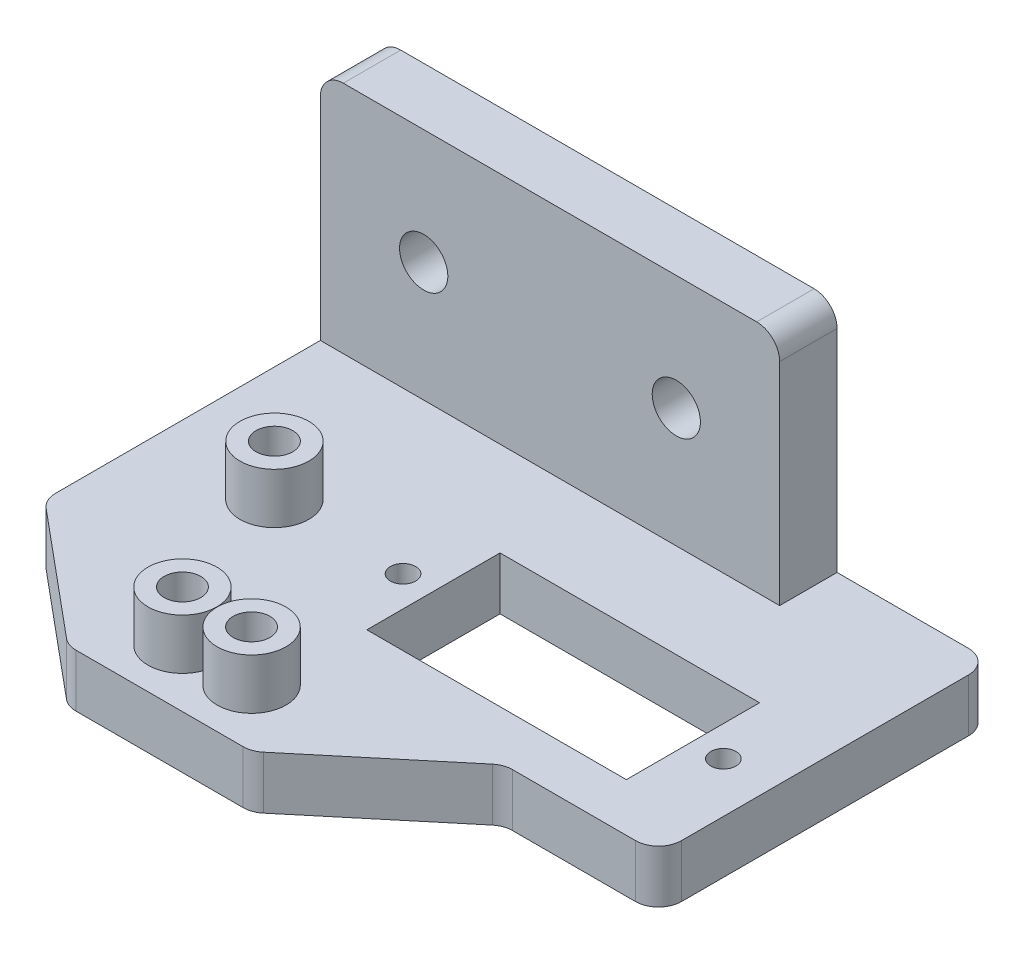
SolidWorks part; units mm, degrees
ref_plane "Front Plane" through (0, 0, 0) normal (0, 0, 1) x (1, 0, 0)
ref_plane "Top Plane" through (0, 0, 0) normal (0, 1, 0) x (1, 0, 0)
ref_plane "Right Plane" through (0, 0, 0) normal (1, 0, 0) x (0, 0, -1)
sketch "Sketch1" plane through (0, 0, 0) normal (0, 1, 0) x (1, 0, 0)
  line L1 (0, 0) -> (50, 0)
  line L2 (0, 0) -> (0, -35)
  line L3 (0, -35) -> (50, -35)
  line L4 (50, 0) -> (50, -35)
  dimension "D1" = 35
  dimension "D2" = 50
extrude "Boss-Extrude1" add sketch "Sketch1" along normal blind 4.6
sketch "Sketch2" plane through (0, 4.6, 0) normal (0, 1, 0) x (1, 0, 0)
  line L0 (0, -17.5) -> (8.0268, -17.5) construction
  line L1 (22.4, -11.7) -> (45, -11.7)
  line L2 (22.4, -11.7) -> (22.4, -23.3)
  line L3 (22.4, -23.3) -> (45, -23.3)
  line L4 (45, -11.7) -> (45, -23.3)
  line L6 (0, -35) -> (50, -35) construction
  line L7 (50, 0) -> (0, 0) construction
  line L8 (50, -35) -> (50, 0) construction
  dimension "D1" = 11.6
  dimension "D2" = 22.6
  dimension "D3" = 5
extrude "Cut-Extrude1" cut sketch "Sketch2" against normal through all
sketch "Sketch3" plane through (0, 4.6, 0) normal (0, 1, 0) x (1, 0, 0)
  line L0 (22.4, -11.7) -> (22.4, -23.3) construction
  line L3 (0, -17.5) -> (2.3023, -17.5) construction
  line L5 (50, 0) -> (0, 0) construction
  line L6 (0, -35) -> (50, -35) construction
  circle A0 centre (8.55, -17.5) radius 3
  circle A1 centre (15.54, -32.5) radius 3
  circle A2 centre (21.56, -32.5) radius 3
  point P14 (0, 0)
  dimension "D1" = 6
  dimension "D2" = 13.85
  dimension "D3" = 6.99
  dimension "D4" = 15
  dimension "D5" = 6.02
extrude "Boss-Extrude2" add sketch "Sketch3" along normal blind 4.4
sketch "Sketch5" plane through (0, 4.6, 0) normal (0, 1, 0) x (1, 0, 0)
  line L0 (50, -35) -> (50, 0) construction
  line L1 (0, -35) -> (50, -35)
  line L2 (0, -35) -> (0, -37.5)
  line L3 (0, -37.5) -> (50, -37.5)
  line L4 (50, -35) -> (50, -37.5)
  dimension "D1" = 2.5
extrude "Boss-Extrude3" add sketch "Sketch5" against normal blind 4.6
sketch "Sketch6" plane through (0, 9, 0) normal (0, 1, 0) x (1, 0, 0)
  circle A0 centre (8.55, -17.5) radius 1.6
  circle A1 centre (15.54, -32.5) radius 1.6
  circle A2 centre (21.56, -32.5) radius 1.6
  dimension "D1" = 3.2
extrude "Cut-Extrude2" cut sketch "Sketch6" against normal through all
sketch "Sketch7" plane through (0, 4.6, 0) normal (0, 1, 0) x (1, 0, 0)
  line L0 (50, -37.5) -> (50, 0) construction
  line L1 (0, 0) -> (50, 0)
  line L2 (0, 0) -> (0, 1.5)
  line L3 (0, 1.5) -> (50, 1.5)
  line L4 (50, 0) -> (50, 1.5)
  dimension "D1" = 1.5
extrude "Boss-Extrude4" add sketch "Sketch7" against normal blind 4.6
sketch "Sketch8" plane through (0, 4.6, 0) normal (0, 1, 0) x (1, 0, 0)
  line L0 (0, -37.5) -> (50, -37.5) construction
  line L1 (0, 1.5) -> (-1.45, 1.5)
  line L2 (0, 1.5) -> (0, -37.5)
  line L3 (0, -37.5) -> (-1.45, -37.5)
  line L4 (-1.45, 1.5) -> (-1.45, -37.5)
  dimension "D1" = 1.45
extrude "Boss-Extrude5" add sketch "Sketch8" against normal blind 4.6
sketch "Sketch9" plane through (0, 4.6, 0) normal (0, 1, 0) x (1, 0, 0)
  line L1 (-1.45, 1.5) -> (38.55, 1.5)
  line L2 (-1.45, 1.5) -> (-1.45, -3.5)
  line L3 (-1.45, -3.5) -> (38.55, -3.5)
  line L4 (38.55, 1.5) -> (38.55, -3.5)
  dimension "D1" = 5
  dimension "D2" = 40
extrude "Boss-Extrude6" add sketch "Sketch9" along normal blind 20.4
sketch "Sketch10" plane through (0, 0, -1.5) normal (0, 0, -1) x (-1, 0, 0)
  line L0 (-38.55, 25) -> (1.45, 25) construction
  line L1 (-38.55, 25) -> (-38.55, 4.6) construction
  line L2 (1.45, 0) -> (1.45, 25) construction
  circle A0 centre (-29.55, 15) radius 2.1
  circle A1 centre (-7.55, 15) radius 2.1
  point P8 (0, 0)
  dimension "D3" = 4.2
  dimension "D1" = 10
  dimension "D2" = 9
  dimension "D4" = 9
extrude "Cut-Extrude3" cut sketch "Sketch10" against normal through all
sketch "Sketch11" plane through (0, 4.6, 0) normal (0, 1, 0) x (1, 0, 0)
  line L0 (45, -23.3) -> (45, -11.7) construction
  line L1 (0.6163, -17.5) -> (14.3571, -17.5) construction
  line L2 (45, -11.7) -> (22.4, -11.7) construction
  line L3 (22.4, -23.3) -> (45, -23.3) construction
  line L4 (22.4, -11.7) -> (22.4, -23.3) construction
  circle A0 centre (47.65, -17.5) radius 1.1
  circle A1 centre (19.75, -17.5) radius 1.1
  point P12 (0, 0)
  point P13 (0, 0)
  dimension "D1" = 2.2
  dimension "D2" = 2.65
  dimension "D3" = 2.65
extrude "Cut-Extrude4" cut sketch "Sketch11" against normal through all
sketch "Sketch12" plane through (0, 4.6, 0) normal (0, 1, 0) x (1, 0, 0)
  line L0 (-1.45, -37.5) -> (50, -37.5) construction
  line L1 (50, 1.5) -> (52, 1.5)
  line L2 (50, 1.5) -> (50, -37.5)
  line L3 (50, -37.5) -> (52, -37.5)
  line L4 (52, 1.5) -> (52, -37.5)
  dimension "D1" = 2
extrude "Boss-Extrude7" add sketch "Sketch12" against normal blind 4.6
sketch "Sketch13" plane through (0, 4.6, 0) normal (0, 1, 0) x (1, 0, 0)
  line L0 (10.54, -37.5) -> (-1.45, -27.5)
  line L1 (-1.45, -37.5) -> (52, -37.5) construction
  line L2 (-1.45, -3.5) -> (-1.45, -37.5) construction
  line L3 (-1.45, -27.5) -> (-1.45, -37.5)
  line L4 (-1.45, -37.5) -> (10.54, -37.5)
  line L5 (26.56, -37.5) -> (38.5496, -27.5)
  line L6 (38.5496, -27.5) -> (52, -27.5)
  line L7 (52, -37.5) -> (52, 1.5) construction
  line L8 (52, -27.5) -> (52, -37.5)
  line L9 (52, -37.5) -> (26.56, -37.5)
  circle A0 centre (15.54, -32.5) radius 1.6 construction
  circle A1 centre (21.56, -32.5) radius 1.6 construction
  point P19 (0, 0)
  dimension "D1" = 5
  dimension "D2" = 5
  dimension "D3" = 10
  dimension "D4" = 39.83
extrude "Cut-Extrude5" cut sketch "Sketch13" against normal through all
fillet "Fillet1" radius 2 6 edges at (52, 2.3, -1.5) (52, 2.3, 27.5) (26.56, 2.3, 37.5) (38.5496, 2.3, 27.5) (10.54, 2.3, 37.5) (-1.45, 2.3, 27.5)
fillet "Fillet2" radius 2 2 edges at (38.55, 25, 1) (-1.45, 25, 1)
